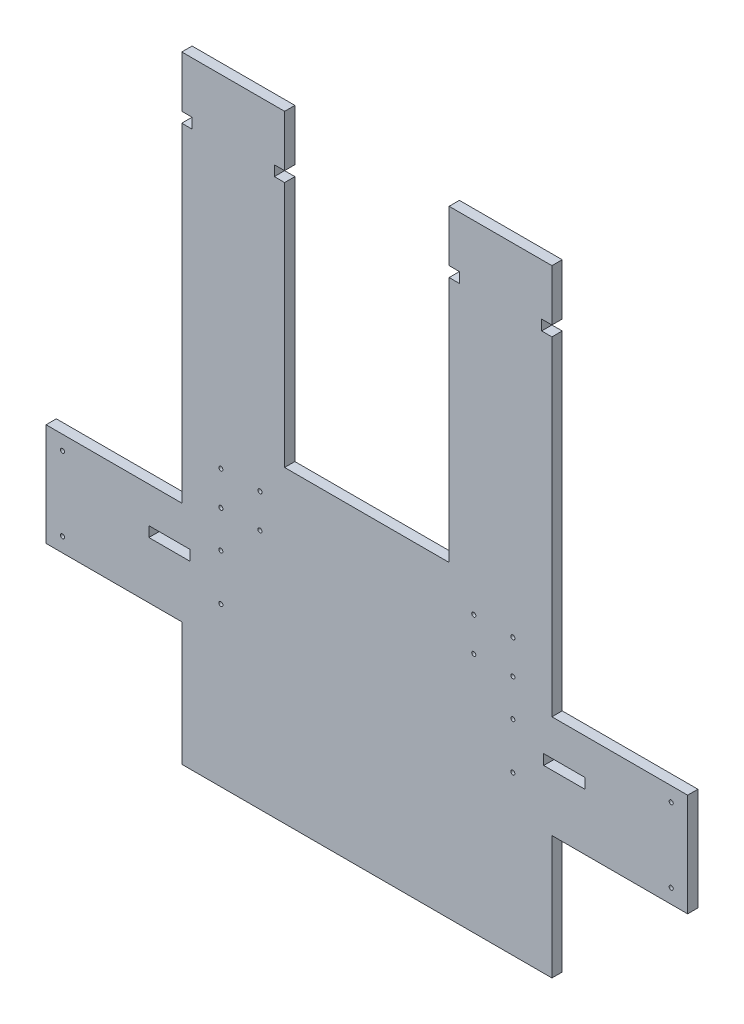
SolidWorks part; units mm, degrees
ref_plane "Front Plane" through (0, 0, 0) normal (0, 0, 1) x (1, 0, 0)
ref_plane "Top Plane" through (0, 0, 0) normal (0, 1, 0) x (1, 0, 0)
ref_plane "Right Plane" through (0, 0, 0) normal (1, 0, 0) x (0, 0, -1)
sketch "Sketch1" plane through (0, 0, 0) normal (0, 0, 1) x (1, 0, 0)
  line L0 (0, 150) -> (180, 150) construction
  line L1 (0, 0) -> (180, 0)
  line L2 (0, 0) -> (0, 300)
  line L3 (0, 300) -> (180, 300) construction
  line L4 (180, 0) -> (180, 300)
  line L5 (0, 300) -> (50, 300)
  line L6 (50, 300) -> (50, 150)
  line L7 (-66, 110) -> (0, 60) construction
  line L8 (0, 110) -> (-66, 110)
  line L9 (0, 110) -> (0, 60)
  line L10 (0, 60) -> (-66, 60)
  line L11 (-66, 110) -> (-66, 60)
  line L12 (0, 110) -> (-66, 60) construction
  line L13 (-33, 85) -> (-66, 85) construction
  line L14 (90, 150) -> (90, 0) construction
  line L15 (180, 110) -> (246, 110)
  line L16 (180, 110) -> (246, 60) construction
  line L17 (246, 110) -> (180, 60) construction
  line L18 (180, 60) -> (246, 60)
  line L19 (213, 85) -> (246, 85) construction
  line L20 (246, 110) -> (246, 60)
  line L21 (11, 117.5) -> (46, 117.5) construction
  line L22 (50, 150) -> (85, 150) construction
  line L23 (50, 150) -> (50, 110) construction
  line L24 (50, 110) -> (85, 110) construction
  line L25 (85, 150) -> (85, 110) construction
  line L26 (11, 150) -> (46, 150) construction
  line L27 (11, 150) -> (11, 110) construction
  line L28 (11, 110) -> (46, 110) construction
  line L29 (46, 150) -> (46, 110) construction
  line L30 (11, 134) -> (46, 134) construction
  line L31 (19, 150) -> (19, 110) construction
  line L32 (38, 150) -> (38, 110) construction
  line L33 (50, 150) -> (130, 150)
  line L34 (130, 300) -> (130, 150)
  line L35 (180, 300) -> (130, 300)
  circle A0 centre (19, 134) radius 1
  circle A1 centre (38, 134) radius 1
  circle A2 centre (19, 117.5) radius 1
  circle A3 centre (38, 117.5) radius 1
  circle A4 centre (161, 117.5) radius 1
  circle A5 centre (142, 117.5) radius 1
  circle A6 centre (142, 134) radius 1
  circle A7 centre (161, 134) radius 1
  point P7 (90, 150)
  dimension "D17" = 2
  dimension "D18" = 2
  dimension "D19" = 2
  dimension "D20" = 2
  dimension "D1" = 180
  dimension "D2" = 300
  dimension "D3" = 150
  dimension "D4" = 156
  dimension "D5" = 50
  dimension "D6" = 85
  dimension "D7" = 35
  dimension "D8" = 5
  dimension "D9" = 40
  dimension "D10" = 40
  dimension "D11" = 4
  dimension "D12" = 35
  dimension "D13" = 7.5
  dimension "D14" = 24
  dimension "D15" = 8
  dimension "D16" = 8
extrude "Boss-Extrude1" add sketch "Sketch1" along normal blind 5
sketch "Sketch2" plane through (0, 0, 5) normal (0, 0, 1) x (1, 0, 0)
  line L0 (-66, 110) -> (-66, 60) construction
  line L1 (-66, 110) -> (-51, 110) construction
  line L2 (-66, 110) -> (-66, 60) construction
  line L3 (-66, 60) -> (-51, 60) construction
  line L4 (-51, 110) -> (-51, 60) construction
  line L5 (0, 60) -> (-66, 60) construction
  line L6 (-58, 110) -> (-58, 60) construction
  line L7 (90, 150) -> (90, 0) construction
  line L8 (0, 0) -> (180, 0) construction
  line L9 (50, 150) -> (130, 150) construction
  circle A0 centre (-58, 103) radius 1
  circle A1 centre (-58, 67) radius 1
  circle A2 centre (238, 67) radius 1
  circle A3 centre (238, 103) radius 1
  dimension "D4" = 2
  dimension "D5" = 7
  dimension "D7" = 2
  dimension "D1" = 50
  dimension "D2" = 15
  dimension "D3" = 7
  dimension "D6" = 7
extrude "Cut-Extrude1" cut sketch "Sketch2" against normal through all
sketch "Sketch3" plane through (0, 0, 5) normal (0, 0, 1) x (1, 0, 0)
  line L0 (-16, 92.5) -> (4, 87.5) construction
  line L1 (-16, 92.5) -> (4, 92.5)
  line L2 (-16, 92.5) -> (-16, 87.5)
  line L3 (-16, 87.5) -> (4, 87.5) construction
  line L4 (4, 92.5) -> (4, 87.5)
  line L5 (-16, 87.5) -> (4, 92.5) construction
  line L6 (19, 74.5) -> (19, 99.5) construction
  line L7 (-66, 110) -> (-66, 60) construction
  line L8 (0, 110) -> (-66, 110) construction
  line L9 (-16, 74.5) -> (4, 74.5) construction
  line L10 (-16, 87.5) -> (4, 87.5)
  line L11 (-16, 87.5) -> (-16, 37.5) construction
  line L12 (-16, 37.5) -> (4, 37.5) construction
  line L13 (4, 87.5) -> (4, 37.5) construction
  line L14 (4, 74.5) -> (19, 74.5) construction
  line L15 (90, 0) -> (90, 150) construction
  line L16 (0, 0) -> (180, 0) construction
  line L17 (50, 150) -> (130, 150) construction
  line L18 (196, 92.5) -> (196, 87.5)
  line L19 (196, 87.5) -> (176, 87.5)
  line L20 (176, 92.5) -> (176, 87.5)
  line L21 (196, 92.5) -> (176, 92.5)
  circle A0 centre (19, 77) radius 1
  circle A1 centre (19, 99.5) radius 1
  circle A2 centre (161, 77) radius 1
  circle A3 centre (161, 99.5) radius 1
  point P4 (-6, 90)
  dimension "D9" = 2
  dimension "D10" = 2
  dimension "D11" = 5
  dimension "D12" = 22.5
  dimension "D1" = 60
  dimension "D2" = 20
  dimension "D3" = 20
  dimension "D4" = 5
  dimension "D5" = 50
  dimension "D6" = 13
  dimension "D7" = 15
  dimension "D8" = 25
extrude "Cut-Extrude2" cut sketch "Sketch3" against normal through all
sketch "Sketch4" plane through (0, 0, 5) normal (0, 0, 1) x (1, 0, 0)
  line L0 (0, 110) -> (0, 300) construction
  line L1 (0, 275) -> (5, 275)
  line L2 (0, 275) -> (0, 270)
  line L3 (0, 270) -> (5, 270)
  line L4 (5, 275) -> (5, 270)
  line L5 (0, 300) -> (50, 300) construction
  line L6 (50, 300) -> (50, 150) construction
  line L7 (50, 270) -> (45, 270)
  line L8 (50, 270) -> (50, 275)
  line L9 (50, 275) -> (45, 275)
  line L10 (45, 270) -> (45, 275)
  line L11 (90, 150) -> (90, 275) construction
  line L12 (50, 150) -> (130, 150) construction
  line L13 (135, 270) -> (135, 275)
  line L14 (130, 275) -> (135, 275)
  line L15 (130, 270) -> (130, 275)
  line L16 (130, 270) -> (135, 270)
  line L17 (175, 275) -> (175, 270)
  line L18 (180, 270) -> (175, 270)
  line L19 (180, 275) -> (180, 270)
  line L20 (180, 275) -> (175, 275)
  dimension "D1" = 5
  dimension "D2" = 5
  dimension "D3" = 25
  dimension "D4" = 5
extrude "Cut-Extrude3" cut sketch "Sketch4" against normal through all
